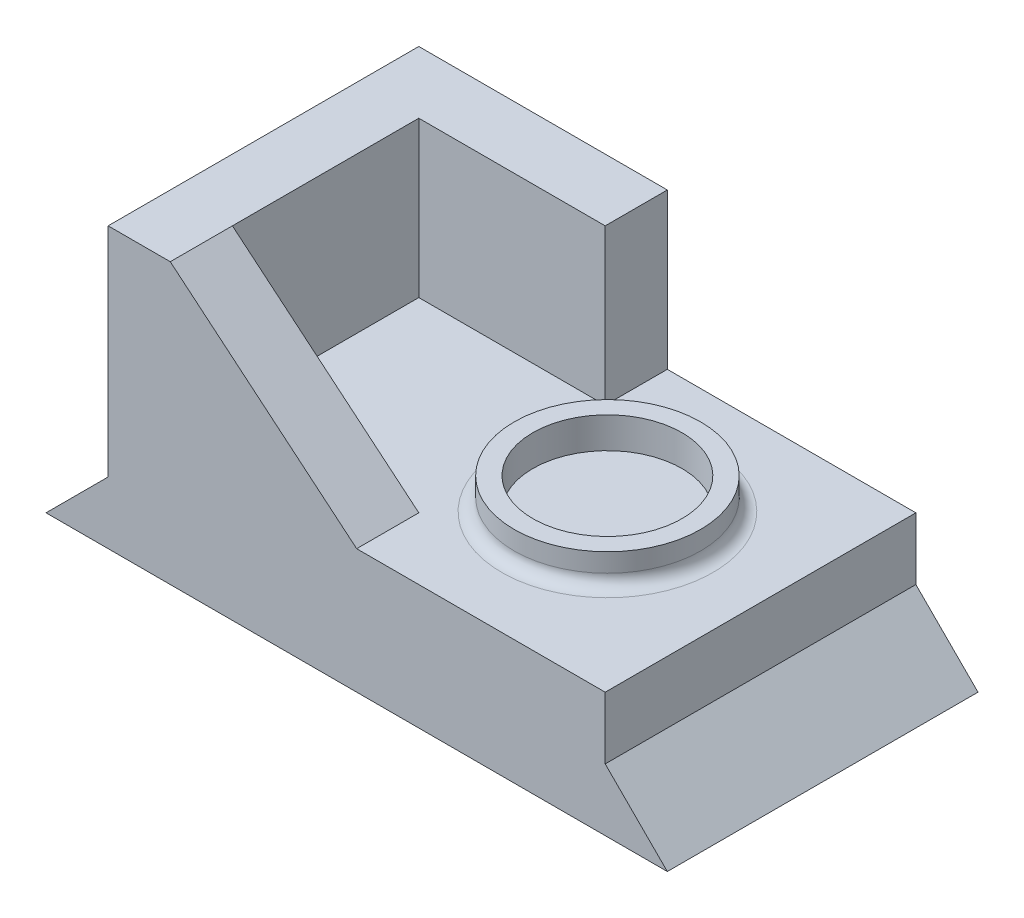
SolidWorks part; units mm, degrees
material "Alliage 1060"
ref_plane "Plan de face" through (0, 0, 0) normal (0, 0, 1) x (1, 0, 0)
ref_plane "Plan de dessus" through (0, 0, 0) normal (0, 1, 0) x (1, 0, 0)
ref_plane "Plan de droite" through (0, 0, 0) normal (1, 0, 0) x (0, 0, -1)
sketch "Esquisse2" plane through (0, 0, 0) normal (0, 0, 1) x (1, 0, 0)
  line L0 (0, 0) -> (100, 0)
  line L1 (100, 0) -> (100, 20)
  line L2 (100, 20) -> (50, 20)
  line L3 (50, 20) -> (50, 45)
  line L4 (50, 45) -> (0, 45)
  line L5 (0, 45) -> (0, 0)
  dimension "D1" = 100
  dimension "D2" = 50
  dimension "D3" = 20
  dimension "D4" = 45
extrude "Boss.-Extru.1" add sketch "Esquisse2" against normal blind 50
sketch "Esquisse3" plane through (0, 0, 0) normal (0, 0, 1) x (1, 0, 0)
  line L0 (0, 45) -> (10, 45)
  line L1 (50, 45) -> (0, 45) construction
  line L2 (10, 45) -> (10, 10)
  line L3 (10, 10) -> (0, 0)
  line L4 (0, 0) -> (0, 45)
  dimension "D1" = 10
  dimension "D2" = 10
extrude "Enlèv. mat.-Extru.1" cut sketch "Esquisse3" against normal through all
sketch "Esquisse4" plane through (0, 0, 0) normal (0, 0, 1) x (1, 0, 0)
  line L0 (100, 20) -> (90, 20)
  line L1 (100, 20) -> (50, 20) construction
  line L2 (90, 20) -> (90, 10)
  line L3 (90, 10) -> (100, 0)
  line L4 (100, 0) -> (100, 20)
  dimension "D1" = 10
  dimension "D2" = 10
extrude "Enlèv. mat.-Extru.2" cut sketch "Esquisse4" against normal through all
sketch "Esquisse5" plane through (50, 0, 0) normal (1, 0, 0) x (0, 0, -1)
  line L0 (10, 45) -> (10, 20)
  line L1 (50, 45) -> (0, 45) construction
  line L2 (50, 20) -> (0, 20) construction
  line L3 (10, 20) -> (40, 20)
  line L4 (40, 20) -> (40, 45)
  line L5 (40, 45) -> (10, 45)
  line L6 (0, 20) -> (0, 45) construction
  line L7 (50, 20) -> (50, 45) construction
  dimension "D1" = 10
  dimension "D2" = 10
extrude "Enlèv. mat.-Extru.3" cut sketch "Esquisse5" against normal blind 30
sketch "Esquisse6" plane through (0, 0, 0) normal (0, 0, 1) x (1, 0, 0)
  line L0 (50, 45) -> (50, 20)
  line L1 (50, 20) -> (20, 45)
  line L2 (50, 45) -> (10, 45) construction
  line L3 (20, 45) -> (50, 45)
  dimension "D1" = 30
extrude "Enlèv. mat.-Extru.4" cut sketch "Esquisse6" against normal blind 10 contours L3 L0 L1
sketch "Esquisse7" plane through (0, 20, 0) normal (0, 1, 0) x (1, 0, 0)
  line L0 (65, 58.0882) -> (65, -7.3741) construction
  line L1 (90, 50) -> (90, 0) construction
  line L2 (44.3735, 25) -> (106.8062, 25) construction
  line L3 (90, 0) -> (50, 0) construction
  circle A0 centre (65, 25.3571) radius 12
  circle A1 centre (65, 25.3571) radius 15
  dimension "D3" = 24
  dimension "D4" = 30
  dimension "D1" = 25
  dimension "D2" = 25
extrude "Boss.-Extru.2" add sketch "Esquisse7" along normal blind 5
fillet "Congé1" radius 2 1 edges at (50, 20, -25.3571)
